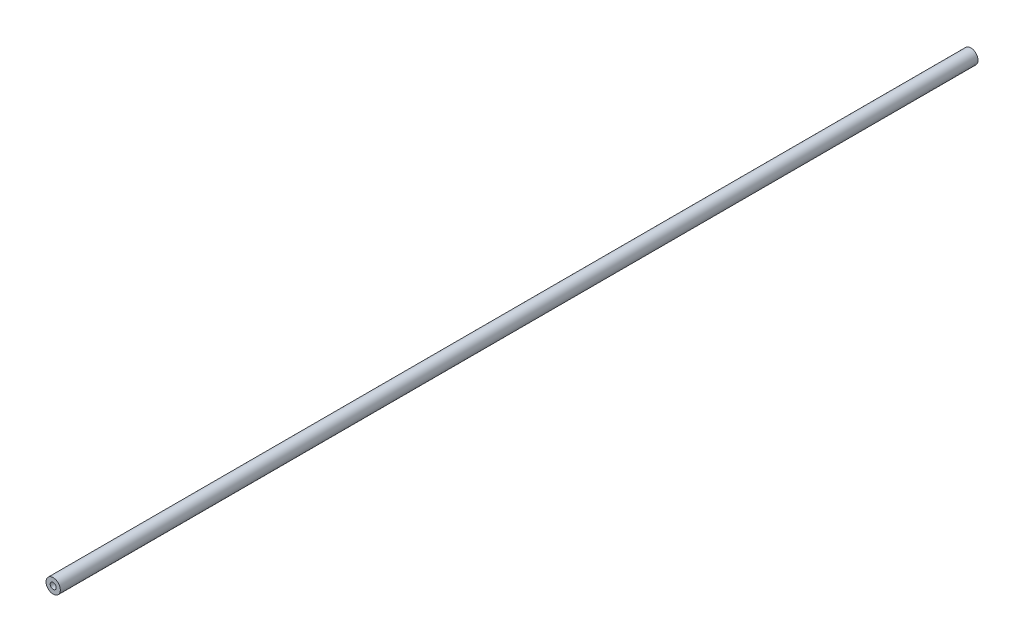
SolidWorks part; units mm, degrees
material "6061-T6 (SS)"
ref_plane "Front Plane" through (0, 0, 0) normal (0, 0, 1) x (1, 0, 0)
ref_plane "Top Plane" through (0, 0, 0) normal (0, 1, 0) x (1, 0, 0)
ref_plane "Right Plane" through (0, 0, 0) normal (1, 0, 0) x (0, 0, -1)
sketch "Sketch1" plane through (0, 0, 0) normal (0, 0, 1) x (1, 0, 0)
  circle A1 centre (0, 0) radius 4.7625
  dimension "D2" = 9.525
extrude "Boss-Extrude1" add sketch "Sketch1" along normal mid plane 609.6
hole_wizard "#10-32 Tapped Hole1" positions "3DSketch1" profile "Sketch2" tap size "#10-32" standard "ANSI Inch"
sketch3d "3DSketch1"
  line L0 (0, 0, 304.8) -> (0, 0, -304.8) construction
  point P0 (0, 0, -304.8)
  point P4 (0, 0, 304.8)
sketch "Sketch2" plane through (0, 0, -304.8) normal (1, 0, 0) x (0, 1, 0)
  line L0 (0, 0) -> (0, 13.2428)
  line L1 (0, 13.2428) -> (2.0193, 12.0294)
  line L2 (2.0193, 12.0294) -> (2.0193, 0)
  line L5 (2.0193, 0) -> (0, 0)
  line L10 (0, 13.2428) -> (-2.0193, 12.0294) construction
  line L11 (0, -6.35) -> (0, 107.95) construction
  dimension "Tap Drill Dia." = 4.0386
  dimension "Tap Drill Depth" = 12.0294
  dimension "Drill Angle" = 118
cosmetic thread "Hole Thread1" parameters "D1"=9.652, "D2"=4.826
cosmetic thread "Hole Thread2" parameters "D1"=9.652, "D2"=4.826
